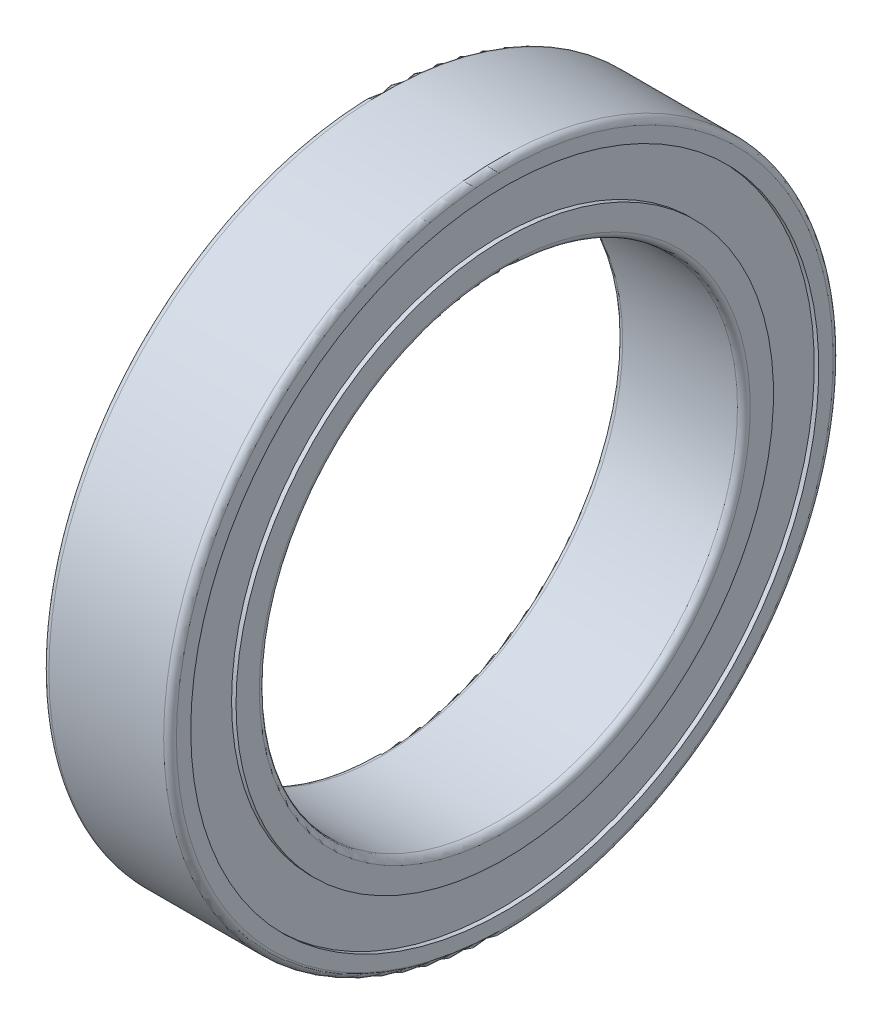
SolidWorks part; units mm, degrees
ref_plane "Front Plane" through (0, 0, 0) normal (0, 0, 1) x (1, 0, 0)
ref_plane "Top Plane" through (0, 0, 0) normal (0, 1, 0) x (1, 0, 0)
ref_plane "Right Plane" through (0, 0, 0) normal (1, 0, 0) x (0, 0, -1)
sketch "Sketch1" plane through (0, 0, 0) normal (0, 0, 1) x (1, 0, 0)
  line L0 (0, 0) -> (4, 0) construction
  line L1 (0, 7.5) -> (4, 7.5)
  line L2 (0, 10.5) -> (4, 10.5)
  line L3 (0, 10.5) -> (0, 9.85)
  line L4 (0, 9.85) -> (0.14, 9.85)
  line L5 (4, 10.5) -> (4, 9.85)
  line L6 (0.14, 9.85) -> (0.14, 8.43)
  line L7 (0.14, 8.43) -> (0, 8.43)
  line L8 (0, 8.43) -> (0, 7.5)
  line L9 (4, 9.85) -> (3.86, 9.85)
  line L10 (3.86, 9.85) -> (3.86, 8.43)
  line L11 (3.86, 8.43) -> (4, 8.43)
  line L12 (4, 8.43) -> (4, 7.5)
  dimension "D" = 21
  dimension "B" = 4
  dimension "D_s" = 15
  dimension "MSM_1" = 19.7
  dimension "MSM_2" = 16.86
  dimension "MSM_3" = 0.14
revolve "Revolve1" add sketch "Sketch1" angle 360 about L0
fillet "Fillet1" radius 0.2 2 edges at (4, 0, 10.5) (0, 0, 10.5)
fillet "Fillet2" radius 0.2 2 edges at (4, 0, 7.5) (0, 0, 7.5)
